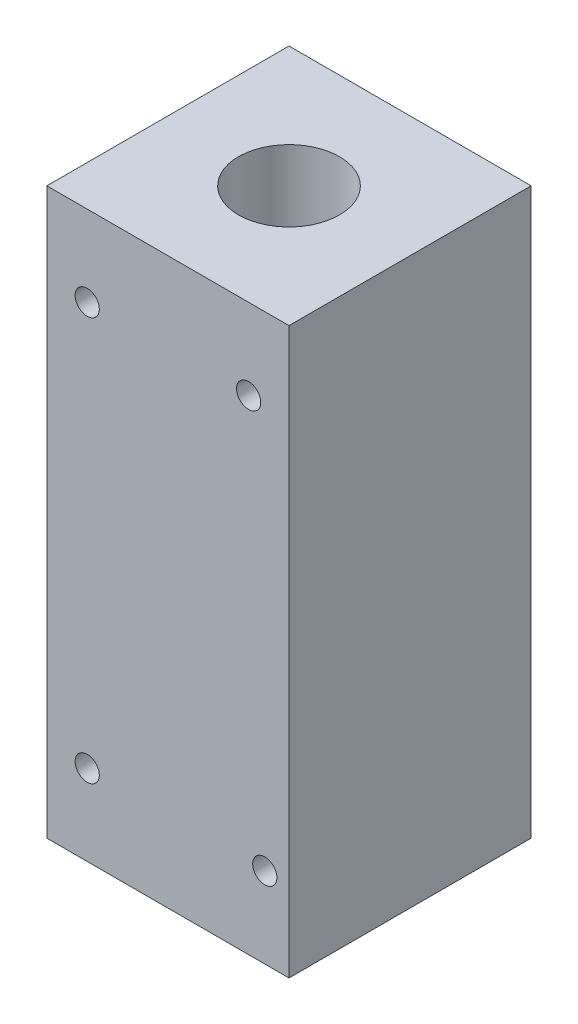
SolidWorks part; units mm, degrees
ref_plane "Plano frontal" through (0, 0, 0) normal (0, 0, 1) x (1, 0, 0)
ref_plane "Plano superior" through (0, 0, 0) normal (0, 1, 0) x (1, 0, 0)
ref_plane "Plano direito" through (0, 0, 0) normal (1, 0, 0) x (0, 0, -1)
sketch "Esboço1" plane through (0, 0, 0) normal (0, 0, 1) x (1, 0, 0)
  line L1 (0, 0) -> (-30, 0)
  line L2 (0, 0) -> (0, 70)
  line L3 (0, 70) -> (-30, 70)
  line L4 (-30, 0) -> (-30, 70)
  dimension "D1" = 30
  dimension "D2" = 70
extrude "Ressalto-extrusão1" add sketch "Esboço1" along normal blind 30
sketch "Esboço3" plane through (0, 70, 0) normal (0, 1, 0) x (1, 0, 0)
  line L0 (0, -30) -> (0, 0) construction
  line L1 (0, -30) -> (-30, -30) construction
  circle A0 centre (-15, -15) radius 6.255
  dimension "D3" = 12.51
  dimension "D1" = 15
  dimension "D2" = 15
extrude "Corte-extrusão2" cut sketch "Esboço3" against normal through all
sketch "Esboço4" plane through (0, 0, 0) normal (0, 0, -1) x (-1, 0, 0)
  line L0 (0, 70) -> (30, 70) construction
  line L1 (30, 0) -> (0, 0) construction
  line L2 (30, 70) -> (30, 0) construction
  line L3 (0, 0) -> (0, 70) construction
  circle A0 centre (5, 60) radius 1.5
  circle A1 centre (3, 10) radius 1.5
  circle A2 centre (25, 60) radius 1.5
  circle A3 centre (25, 10) radius 1.5
  dimension "D1" = 3
  dimension "D2" = 3
  dimension "D3" = 3
  dimension "D4" = 3
  dimension "D5" = 10
  dimension "D6" = 10
  dimension "D7" = 10
  dimension "D8" = 10
  dimension "D9" = 5
  dimension "D10" = 5
  dimension "D11" = 5
  dimension "D12" = 3
extrude "Corte-extrusão3" cut sketch "Esboço4" against normal through all
sketch "Esboço5" plane through (-30, 0, 0) normal (-1, 0, 0) x (0, 0, 1)
  line L0 (30, 70) -> (0, 70) construction
  line L2 (30, 0) -> (0, 0) construction
  circle A0 centre (2.9245, 50) radius 1.5
  circle A1 centre (2.9245, 20) radius 1.5
  dimension "D1" = 3
  dimension "D2" = 3
  dimension "D3" = 20
  dimension "D4" = 20
extrude "Corte-extrusão4" cut sketch "Esboço5" against normal blind 10
